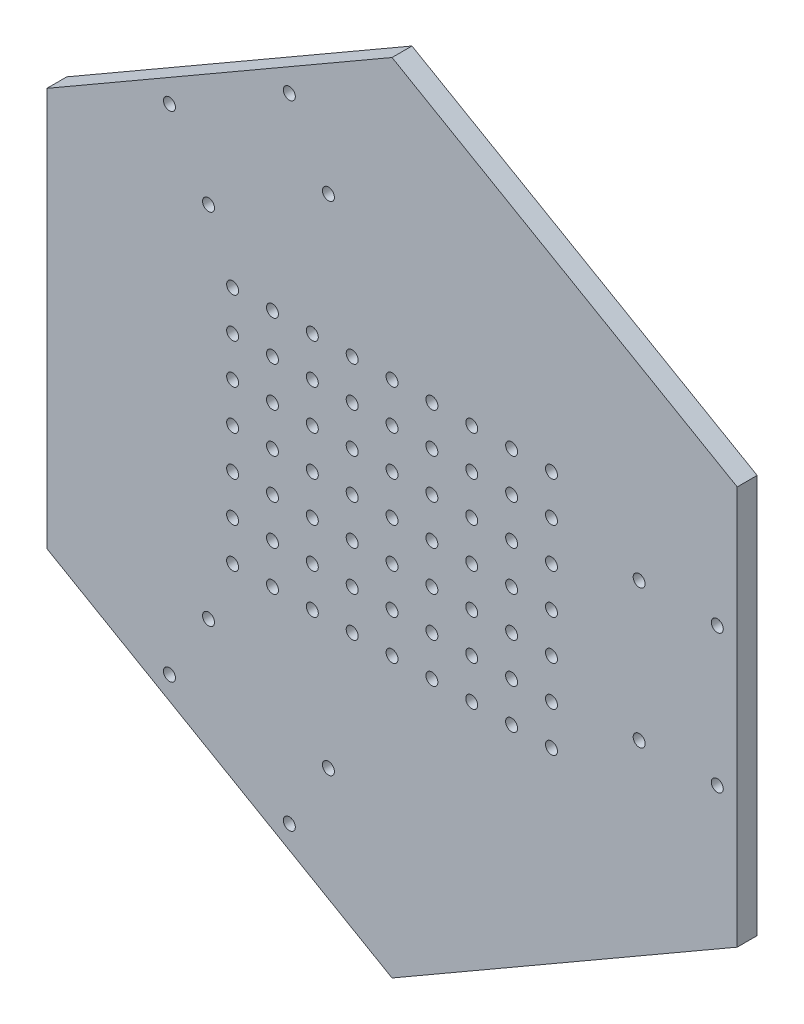
SolidWorks part; units mm, degrees
ref_plane "前视基准面" through (0, 0, 0) normal (0, 0, 1) x (1, 0, 0)
ref_plane "上视基准面" through (0, 0, 0) normal (0, 1, 0) x (1, 0, 0)
ref_plane "右视基准面" through (0, 0, 0) normal (1, 0, 0) x (0, 0, -1)
sketch "草图1" plane through (0, 0, 0) normal (0, 0, 1) x (1, 0, 0)
  line L1 (86.6025, 50) -> (0, 100)
  line L2 (0, 100) -> (-86.6025, 50)
  line L3 (-86.6025, 50) -> (-86.6025, -50)
  line L4 (-86.6025, -50) -> (0, -100)
  line L5 (0, -100) -> (86.6025, -50)
  line L6 (86.6025, -50) -> (86.6025, 50)
  circle A0 centre (0, 0) radius 86.6025 construction
  dimension "D1" = 100
extrude "凸台-拉伸1" add sketch "草图1" along normal blind 5
sketch "草图2" plane through (0, 0, 0) normal (0, 0, -1) x (-1, 0, 0)
  line L0 (-86.6025, 0) -> (86.6025, 0) construction
  line L1 (-86.6025, -50) -> (-86.6025, 50) construction
  line L2 (86.6025, 50) -> (86.6025, -50) construction
  circle A0 centre (-81.6025, 17.365) radius 1.5
  circle A1 centre (-62.0025, 17.37) radius 1.5
  circle A2 centre (-62.0025, -17.37) radius 1.5
  circle A3 centre (-81.6025, -17.365) radius 1.5
  circle A4 centre (0, 0) radius 25.3025 construction
  circle A5 centre (55.8398, 61.9874) radius 1.5
  circle A6 centre (46.0441, 45.0108) radius 1.5
  circle A7 centre (15.9584, 62.3808) radius 1.5
  circle A8 centre (25.7627, 79.3524) radius 1.5
  circle A9 centre (0, 0) radius 25.3025 construction
  circle A10 centre (25.7627, -79.3524) radius 1.5
  circle A11 centre (15.9584, -62.3808) radius 1.5
  circle A12 centre (46.0441, -45.0108) radius 1.5
  circle A13 centre (55.8398, -61.9874) radius 1.5
  circle A14 centre (0, 0) radius 25.3025 construction
  dimension "D2" = 3
  dimension "D6" = 3
  dimension "D1" = 17.365
  dimension "D3" = 17.37
  dimension "D4" = 19.6
  dimension "D5" = 5
  dimension "D7" = 3
extrude "切除-拉伸1" cut sketch "草图2" against normal blind 5
sketch "草图3" plane through (0, 0, 5) normal (0, 0, 1) x (1, 0, 0)
  line L0 (2.75, 0) -> (-2.75, 0) construction
  line L1 (0, -2.75) -> (0, 2.75) construction
  circle A0 centre (0, 0) radius 1.5
  circle A1 centre (10, 0) radius 1.5
  circle A2 centre (20, 0) radius 1.5
  circle A3 centre (30, 0) radius 1.5
  circle A4 centre (40, 0) radius 1.5
  circle A5 centre (10, 10) radius 1.5
  circle A6 centre (20, 10) radius 1.5
  circle A7 centre (30, 10) radius 1.5
  circle A8 centre (40, 10) radius 1.5
  circle A9 centre (10, 20) radius 1.5
  circle A10 centre (20, 20) radius 1.5
  circle A11 centre (30, 20) radius 1.5
  circle A12 centre (40, 20) radius 1.5
  circle A13 centre (10, 30) radius 1.5
  circle A14 centre (20, 30) radius 1.5
  circle A15 centre (30, 30) radius 1.5
  circle A16 centre (40, 30) radius 1.5
  circle A17 centre (0, 10) radius 1.5
  circle A18 centre (0, 20) radius 1.5
  circle A19 centre (0, 30) radius 1.5
  circle A20 centre (0, -30) radius 1.5
  circle A21 centre (0, -20) radius 1.5
  circle A22 centre (0, -10) radius 1.5
  circle A23 centre (40, -30) radius 1.5
  circle A24 centre (30, -30) radius 1.5
  circle A25 centre (20, -30) radius 1.5
  circle A26 centre (10, -30) radius 1.5
  circle A27 centre (40, -20) radius 1.5
  circle A28 centre (30, -20) radius 1.5
  circle A29 centre (20, -20) radius 1.5
  circle A30 centre (10, -20) radius 1.5
  circle A31 centre (40, -10) radius 1.5
  circle A32 centre (30, -10) radius 1.5
  circle A33 centre (20, -10) radius 1.5
  circle A34 centre (10, -10) radius 1.5
  circle A35 centre (-10, -10) radius 1.5
  circle A36 centre (-20, -10) radius 1.5
  circle A37 centre (-30, -10) radius 1.5
  circle A38 centre (-40, -10) radius 1.5
  circle A39 centre (-10, -20) radius 1.5
  circle A40 centre (-20, -20) radius 1.5
  circle A41 centre (-30, -20) radius 1.5
  circle A42 centre (-40, -20) radius 1.5
  circle A43 centre (-10, -30) radius 1.5
  circle A44 centre (-20, -30) radius 1.5
  circle A45 centre (-30, -30) radius 1.5
  circle A46 centre (-40, -30) radius 1.5
  circle A47 centre (-40, 30) radius 1.5
  circle A48 centre (-30, 30) radius 1.5
  circle A49 centre (-20, 30) radius 1.5
  circle A50 centre (-10, 30) radius 1.5
  circle A51 centre (-40, 20) radius 1.5
  circle A52 centre (-30, 20) radius 1.5
  circle A53 centre (-20, 20) radius 1.5
  circle A54 centre (-10, 20) radius 1.5
  circle A55 centre (-40, 10) radius 1.5
  circle A56 centre (-30, 10) radius 1.5
  circle A57 centre (-20, 10) radius 1.5
  circle A58 centre (-10, 10) radius 1.5
  circle A59 centre (-40, 0) radius 1.5
  circle A60 centre (-30, 0) radius 1.5
  circle A61 centre (-20, 0) radius 1.5
  circle A62 centre (-10, 0) radius 1.5
  dimension "D1" = 5
  dimension "D2" = 4
extrude "切除-拉伸2" cut sketch "草图3" against normal through all
